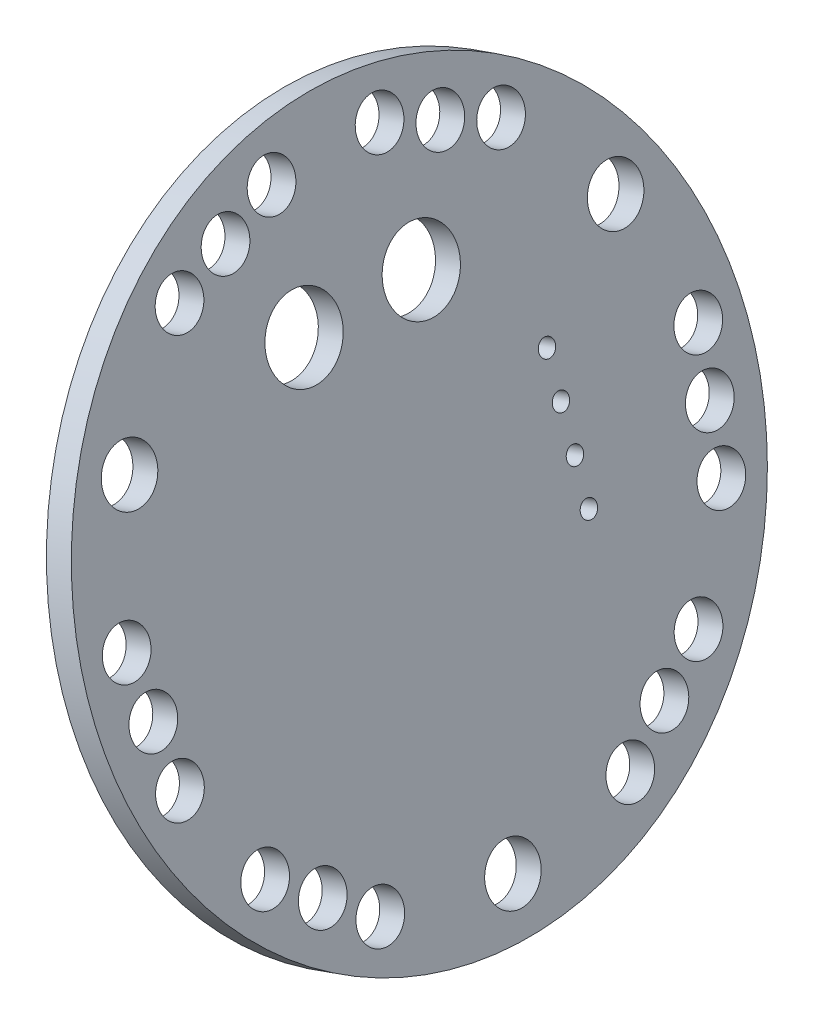
SolidWorks part; units mm, degrees
ref_plane "Front Plane" through (0, 0, 0) normal (0, 0, 1) x (1, 0, 0)
ref_plane "Top Plane" through (0, 0, 0) normal (0, 1, 0) x (1, 0, 0)
ref_plane "Right Plane" through (0, 0, 0) normal (1, 0, 0) x (0, 0, -1)
sketch "Sketch1" plane through (-6.6939, -2.3667, 0) normal (0.9428, 0.3333, 0) x (0, 0, -1)
  circle A0 centre (0, 0) radius 20
  dimension "D1" = 40
extrude "Boss-Extrude1" add sketch "Sketch1" along normal blind 1.6
sketch "Sketch2" plane through (-5.1854, -1.8333, 0) normal (0.9428, 0.3333, 0) x (0, 0, -1)
  circle A0 centre (0, -17) radius 1.625
  circle A1 centre (-14.7224, 8.5) radius 1.625
  circle A2 centre (14.7224, 8.5) radius 1.625
  point P9 (0, 0)
  dimension "D1" = 3
  dimension "D3" = 3.25
  dimension "D2" = 17
extrude "Cut-Extrude1" cut sketch "Sketch2" against normal through all
sketch "Sketch3" plane through (-5.1854, -1.8333, 0) normal (0.9428, 0.3333, 0) x (0, 0, -1)
  line L0 (-9.7392, 14.3666) -> (-3.272, 17.0453) construction
  line L1 (0, 8.163) -> (0, -8.163) construction
  line L2 (-6.5056, 15.706) -> (0, 0) construction
  line L3 (6.5056, 15.706) -> (0, 0) construction
  circle A0 centre (-9.7392, 14.3666) radius 1.4
  circle A1 centre (-3.272, 17.0453) radius 1.4
  circle A2 centre (-6.5056, 15.706) radius 1.4
  circle A3 centre (9.7392, 14.3666) radius 1.4
  circle A4 centre (6.5056, 15.706) radius 1.4
  circle A5 centre (3.272, 17.0453) radius 1.4
  dimension "D1" = 7
  dimension "D2" = 2.8
  dimension "D3" = 17
  dimension "D4" = 45
extrude "Cut-Extrude2" cut sketch "Sketch3" against normal through all
pattern_circular "CirPattern1" count 3 over 360 about axis through (0, 0, 0) along (0.9428, 0.3333, 0) of "Cut-Extrude2"
sketch "Sketch4" plane through (-5.1854, -1.8333, 0) normal (0.9428, 0.3333, 0) x (0, 0, -1)
  line L0 (9, 3.81) -> (9, -3.81) construction
  circle A0 centre (9, 3.81) radius 0.5
  circle A1 centre (9, 1.27) radius 0.5
  circle A2 centre (9, -1.27) radius 0.5
  circle A3 centre (9, -3.81) radius 0.5
  point P2 (9, 0)
  point P3 (0, 0)
  dimension "D1" = 4
  dimension "D3" = 1
  dimension "D2" = 9
  dimension "D4" = 7.62
extrude "Cut-Extrude3" cut sketch "Sketch4" against normal through all
ref_plane "Plane1" through (0, 0, 0) normal (-0.3333, 0.9428, 0) x (0.9428, 0.3333, 0)
sketch "Sketch5" plane through (-5.1854, -1.8333, 0) normal (0.9428, 0.3333, 0) x (0, 0, -1)
  circle A0 centre (-3.65, 10) radius 2.25
  circle A1 centre (3.45, 10) radius 2.25
  dimension "D1" = 4.5
extrude "Cut-Extrude4" cut sketch "Sketch5" against normal through all
